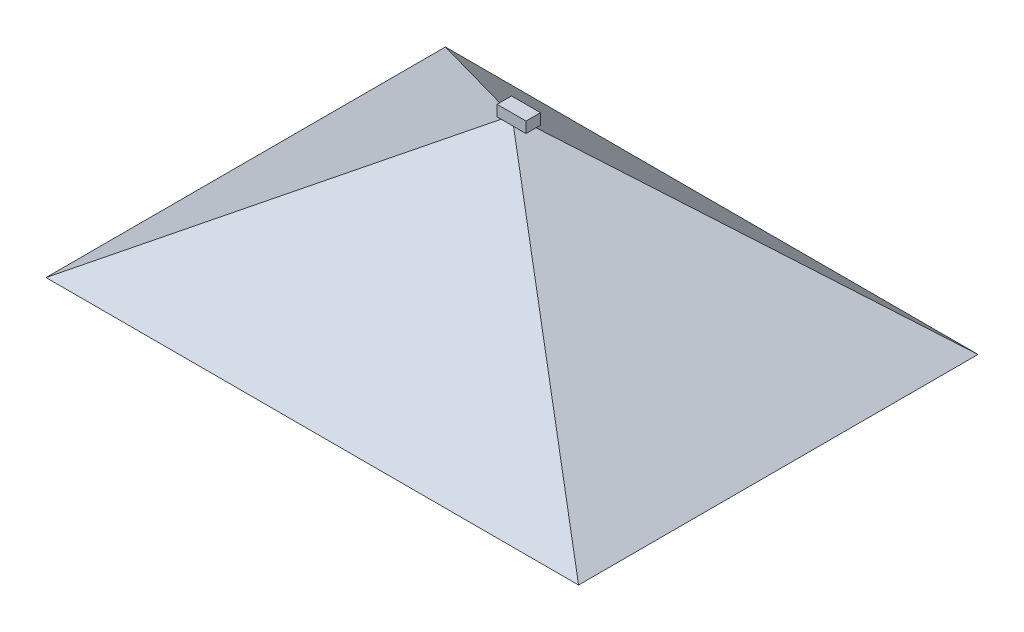
SolidWorks part; units mm, degrees
ref_plane "Front Plane" through (0, 0, 0) normal (0, 0, 1) x (1, 0, 0)
ref_plane "Top Plane" through (0, 0, 0) normal (0, 1, 0) x (1, 0, 0)
ref_plane "Right Plane" through (0, 0, 0) normal (1, 0, 0) x (0, 0, -1)
sketch "Sketch1" plane through (0, 0, 0) normal (0, 1, 0) x (1, 0, 0)
  line L0 (0, 0) -> (0, 37.9406) construction
  line L1 (0, 0) -> (36.3464, 0) construction
  line L3 (-25.4, 12.7) -> (25.4, 12.7)
  line L4 (-25.4, 12.7) -> (-25.4, -12.7)
  line L5 (-25.4, -12.7) -> (25.4, -12.7)
  line L6 (25.4, 12.7) -> (25.4, -12.7)
  dimension "D1" = 50.8
  dimension "D2" = 25.4
extrude "Boss-Extrude1" add sketch "Sketch1" along normal blind 19.05
sketch "Sketch2" plane through (0, 0, 0) normal (0, -1, 0) x (1, 0, 0)
  circle A0 centre (-11.8308, 0) radius 7.635
extrude "Cut-Extrude1" cut sketch "Sketch2" against normal blind 2.54
sketch "Sketch3" plane through (0, 2.54, 0) normal (0, -1, 0) x (1, 0, 0)
  point P0 (-11.8308, 0)
ref_plane "Plane1" through (0, -302.26, 0) normal (0, -1, 0) x (-1, 0, 0)
sketch "Sketch4" plane through (0, -302.26, 0) normal (0, -1, 0) x (-1, 0, 0)
  line L0 (11.8308, 7.635) -> (11.8308, -7.635) construction
  line L1 (-455.5292, 350.52) -> (479.1908, 350.52)
  line L2 (-455.5292, 350.52) -> (-455.5292, -350.52)
  line L3 (-455.5292, -350.52) -> (479.1908, -350.52)
  line L4 (479.1908, 350.52) -> (479.1908, -350.52)
  line L5 (11.8308, 0) -> (17.7885, 0) construction
  circle A0 centre (11.8308, 0) radius 7.635 construction
  circle A1 centre (11.8308, 0) radius 7.635 construction
  dimension "D1" = 701.04
  dimension "D2" = 934.72
loft "Loft1" add profiles "Sketch4", "Sketch3"
